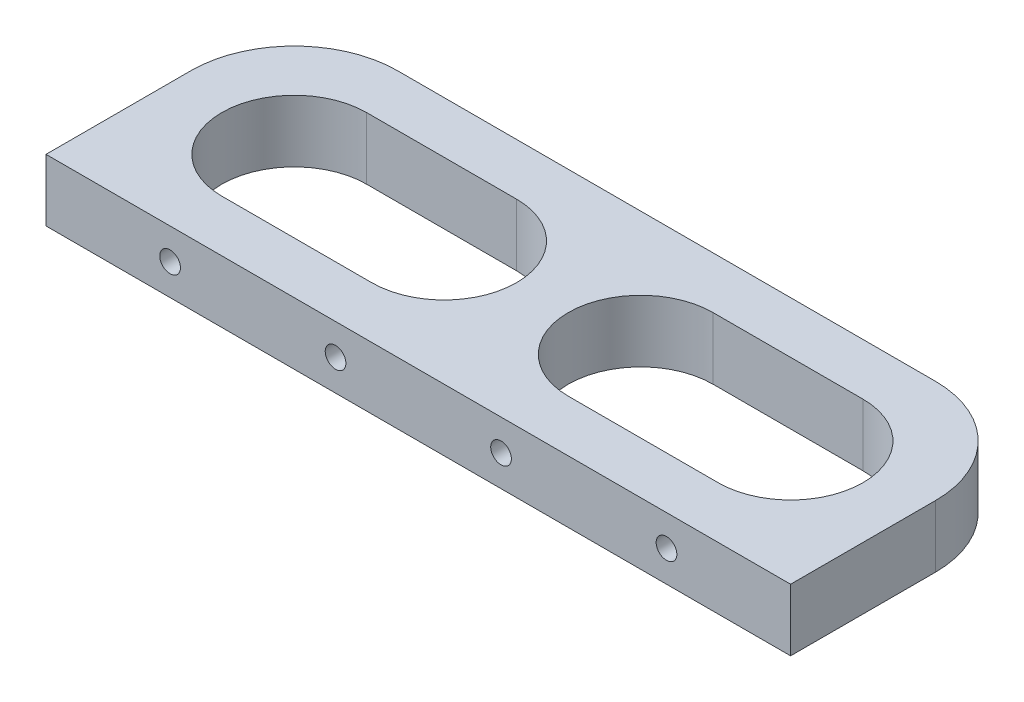
SolidWorks part; units mm, degrees
ref_plane "Front Plane" through (0, 0, 0) normal (0, 0, 1) x (1, 0, 0)
ref_plane "Top Plane" through (0, 0, 0) normal (0, 1, 0) x (1, 0, 0)
ref_plane "Right Plane" through (0, 0, 0) normal (1, 0, 0) x (0, 0, -1)
sketch "Sketch1" plane through (0, 0, 0) normal (0, 1, 0) x (1, 0, 0)
  line L1 (-90, 30) -> (90, 30)
  line L2 (-90, 30) -> (-90, -30)
  line L3 (-90, -30) -> (90, -30)
  line L4 (90, 30) -> (90, -30)
  line L5 (-90, 30) -> (90, -30) construction
  line L6 (-90, -30) -> (90, 30) construction
  point P0 (0, 0)
  dimension "D1" = 60
  dimension "D2" = 180
extrude "Boss-Extrude1" add sketch "Sketch1" along normal blind 15
sketch "Sketch2" plane through (0, 15, 0) normal (0, 1, 0) x (1, 0, 0)
  line L0 (-90, 0) -> (90, 0) construction
  line L4 (-90, 30) -> (-90, -30) construction
  line L5 (90, -30) -> (90, 30) construction
  line L12 (-60, 0) -> (-23.75, 0) construction
  line L13 (-60, 17.5) -> (-23.75, 17.5)
  line L14 (-60, -17.5) -> (-23.75, -17.5)
  line L16 (23.75, 0) -> (60, 0) construction
  line L17 (23.75, 17.5) -> (60, 17.5)
  line L18 (23.75, -17.5) -> (60, -17.5)
  line L20 (90, 30) -> (-90, 30) construction
  arc A10 (-60, 17.5) -> (-60, -17.5) centre (-60, 0) ccw
  arc A11 (-23.75, -17.5) -> (-23.75, 17.5) centre (-23.75, 0) ccw
  arc A12 (23.75, 17.5) -> (23.75, -17.5) centre (23.75, 0) ccw
  arc A13 (60, -17.5) -> (60, 17.5) centre (60, 0) ccw
  point P8 (-41.875, 0)
  point P13 (41.875, 0)
  point P22 (-77.5, 0)
  point P23 (-6.25, 0)
  point P26 (77.5, 0)
  point P27 (6.25, 0)
  dimension "D1" = 12.5
  dimension "D2" = 12.5
  dimension "D3" = 6.25
  dimension "D4" = 12.5
  dimension "D5" = 12.5
  dimension "D6" = 6.25
extrude "Cut-Extrude1" cut sketch "Sketch2" against normal through all
sketch "Sketch3" plane through (0, 0, 30) normal (0, 0, 1) x (1, 0, 0)
  line L0 (-90, 7.5) -> (90, 7.5) construction
  line L1 (-90, 15) -> (-90, 0) construction
  line L2 (90, 15) -> (90, 0) construction
  point P12 (-20, 7.5)
  point P14 (20, 7.5)
  point P16 (-60, 7.5)
  point P18 (60, 7.5)
  point P21 (0, 7.5)
  dimension "D1" = 40
  dimension "D2" = 20
  dimension "D3" = 40
  dimension "D4" = 40
hole_wizard "Tap Drill for M6x1.0 Tap1" positions "Sketch3" profile "Sketch4" hole size "M6x1.0" standard "ANSI Metric"
sketch "Sketch4" plane through (60, 7.5, 30) normal (1, 0, 0) x (0, -1, 0)
  line L0 (0, 0) -> (0, 10.5022)
  line L1 (0, 10.5022) -> (2.5, 9)
  line L2 (2.5, 9) -> (2.5, 0)
  line L5 (2.5, 0) -> (0, 0)
  line L10 (0, 10.5022) -> (-2.5, 9) construction
  line L11 (0, -6.35) -> (0, 107.95) construction
  dimension "Hole Dia." = 5
  dimension "Hole Depth" = 9
  dimension "Drill Angle" = 118
fillet "Fillet1" radius 25 2 edges at (-90, 7.5, -30) (90, 7.5, -30)
sketch "Sketch5" plane through (0, 0, -30) normal (0, 0, -1) x (-1, 0, 0)
  line L0 (-65, 7.5) -> (65, 7.5) construction
  line L1 (-65, 15) -> (-65, 0) construction
  line L2 (65, 0) -> (65, 15) construction
  point P6 (-15, 7.5)
  point P7 (15, 7.5)
  point P8 (45, 7.5)
  point P9 (-45, 7.5)
  point P10 (0, 7.5)
  dimension "D1" = 30
  dimension "D2" = 15
  dimension "D3" = 30
  dimension "D4" = 30
hole_wizard "Tap Drill for M6x1.0 Tap2" positions "Sketch5" profile "Sketch6" hole size "M6x1.0" standard "ANSI Metric"
sketch "Sketch6" plane through (45, 7.5, -30) normal (1, 0, 0) x (0, 1, 0)
  line L0 (0, 0) -> (0, 10.5022)
  line L1 (0, 10.5022) -> (2.5, 9)
  line L2 (2.5, 9) -> (2.5, 0)
  line L5 (2.5, 0) -> (0, 0)
  line L10 (0, 10.5022) -> (-2.5, 9) construction
  line L11 (0, -6.35) -> (0, 107.95) construction
  dimension "Hole Dia." = 5
  dimension "Hole Depth" = 9
  dimension "Drill Angle" = 118
equation "\"D3@Sketch2\"=\"D1@Sketch2\"/2"
equation "\"D2@Sketch2\"=\"D1@Sketch2\""
equation "\"D4@Sketch2\"=\"D1@Sketch2\""
equation "\"D5@Sketch2\"=\"D1@Sketch2\""
equation "\"D6@Sketch2\"=\"D1@Sketch2\"/2"
equation "\"D2@Sketch3\" = \"D1@Sketch3\" / 2"
equation "\"D3@Sketch3\" = \"D1@Sketch3\""
equation "\"D4@Sketch3\" = \"D1@Sketch3\""
equation "\"D2@Sketch5\"=\"D1@Sketch5\"/2"
equation "\"D3@Sketch5\"=\"D1@Sketch5\""
equation "\"D4@Sketch5\"=\"D1@Sketch5\""
